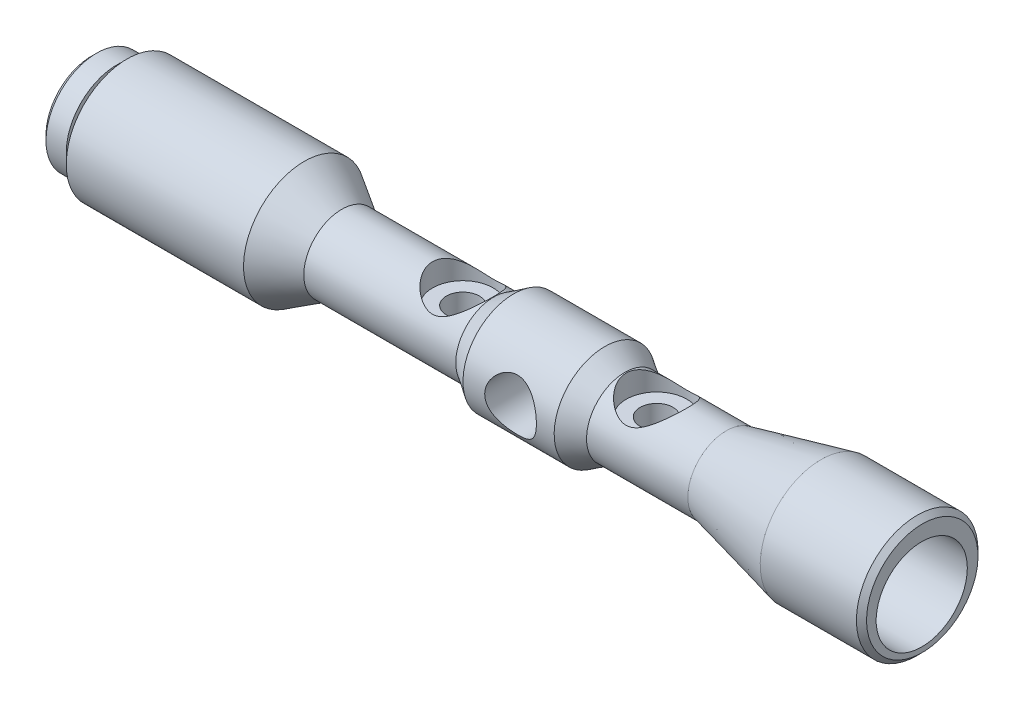
SolidWorks part; units mm, degrees
ref_plane "前视基准面" through (0, 0, 0) normal (0, 0, 1) x (1, 0, 0)
ref_plane "上视基准面" through (0, 0, 0) normal (0, 1, 0) x (1, 0, 0)
ref_plane "右视基准面" through (0, 0, 0) normal (1, 0, 0) x (0, 0, -1)
sketch "草图2" plane through (0, 0, 0) normal (0, 0, 1) x (1, 0, 0)
  line L1 (0, 0) -> (0, 10)
  line L2 (0, 10) -> (5, 10)
  line L3 (5, 10) -> (5, 8.5)
  line L4 (5, 8.5) -> (7, 8.5)
  line L5 (7, 8.5) -> (7, 12)
  line L6 (7, 12) -> (42, 12)
  line L7 (42, 12) -> (49.4, 7.5)
  line L8 (49.4, 7.5) -> (79.4, 7.5)
  line L11 (79.4, 7.5) -> (83.3244, 10)
  line L12 (83.3244, 10) -> (101.3244, 10)
  line L16 (101.3244, 10) -> (105.3, 7.5824)
  line L17 (0, 0) -> (164, 0)
  line L20 (105.3, 7.5824) -> (125.3, 7.5824)
  line L21 (125.3, 7.5824) -> (144, 12)
  line L22 (144, 12) -> (164, 12)
  line L23 (164, 12) -> (164, 0)
  dimension "D1" = 5
  dimension "D10" = 18
  dimension "D2" = 2
  dimension "D3" = 42
  dimension "D4" = 7.4
  dimension "D5" = 10
  dimension "D6" = 30
  dimension "D7" = 12
  dimension "D8" = 7.5
  dimension "D9" = 8.5
  dimension "D11" = 25.9
  dimension "D12" = 10
  dimension "D13" = 12
  dimension "D14" = 20
  dimension "D15" = 18.7
  dimension "D16" = 20
revolve "旋转2" add sketch "草图2" angle 360 about L17
cosmetic thread "装饰螺纹线1" parameters "D2"=17.294
hole_wizard "孔9" positions "草图18" profile "草图19" legacy
sketch "草图18" plane through (0, 0, 0) normal (-1, 0, 0) x (0, 0, 1)
  point P0 (0, 0)
sketch "草图19" plane through (0, 0, 0) normal (0, 1, 0) x (0, 0, 1)
  line L0 (0, 0) -> (0, 52.8868)
  line L1 (0, 52.8868) -> (5, 50)
  line L2 (5, 50) -> (5, 20)
  line L3 (5, 20) -> (7, 20)
  line L4 (7, 0) -> (0, 0)
  line L5 (0, -11.3109) -> (0, 121.1557) construction
  line L6 (0, 52.8868) -> (-5, 50) construction
  line L7 (7, 20) -> (7, 0)
  dimension "直径" = 10
  dimension "深度" = 50
  dimension "柱坑直径" = 14
  dimension "柱坑深度" = 20
  dimension "导头角度" = 120
hole_wizard "M12 螺纹孔1" positions "3D草图7" profile "草图26" tap size "M12" standard "ISO"
sketch3d "3D草图7"
  point P0 (92.712, 0.0036, 10)
sketch "草图26" plane through (92.712, 0.0036, 10) normal (1, 0, 0) x (0, -1, 0.0004)
  line L0 (0, 0) -> (0, 15.0644)
  line L1 (0, 15.0644) -> (5.1, 12)
  line L2 (5.1, 12) -> (5.1, 0)
  line L5 (5.1, 0) -> (0, 0)
  line L10 (0, 15.0644) -> (-5.1, 12) construction
  line L11 (0, -6.35) -> (0, 107.95) construction
  dimension "螺纹孔钻头直径" = 10.2
  dimension "螺纹孔钻头深度" = 12
  dimension "导头角度" = 118
cosmetic thread "孔螺蚊线1" parameters "D1"=12, "D2"=12
chamfer "倒角1" distance 1 angle 45 1 edges at (164, -12, 0)
chamfer "倒角2" distance 1 angle 45 1 edges at (0, -10, 0)
hole_wizard "孔12" positions "草图28" profile "草图27" legacy
sketch "草图28" plane through (164, 0, 0) normal (1, 0, 0) x (0, 0, -1)
  point P0 (-0.1053, -0.9762)
sketch "草图27" plane through (164, -0.9762, 0.1053) normal (0, 1, 0) x (0, 0, -1)
  line L0 (0, 0) -> (0, 42.8868)
  line L1 (0, 42.8868) -> (5, 40)
  line L2 (5, 40) -> (5, 20)
  line L3 (5, 20) -> (9, 20)
  line L4 (9, 0) -> (0, 0)
  line L5 (0, -11.3109) -> (0, 121.1557) construction
  line L6 (0, 42.8868) -> (-5, 40) construction
  line L7 (9, 20) -> (9, 0)
  dimension "直径" = 10
  dimension "深度" = 40
  dimension "柱坑直径" = 18
  dimension "柱坑深度" = 20
  dimension "导头角度" = 120
hole_wizard "孔14" positions "3D草图14" profile "草图38" legacy
sketch3d "3D草图14"
  line L0 (163, 0, 0) -> (39.8271, 0, 0) construction
  circle A0 centre (163, 0, 0) radius 12 construction
  circle A1 centre (164, 0, 0) radius 11 construction
  point P0 (73.3096, 7.5, 0.0003)
  point P8 (151, 0, 0)
  point P14 (175, 0, 0)
  dimension "D1" = 91
sketch "草图38" plane through (73.3096, 7.5, 0.0003) normal (1, 0, 0) x (0, 0, 1)
  line L0 (0, 0) -> (0, 100)
  line L1 (0, 100) -> (3.25, 100)
  line L2 (3.25, 100) -> (3.25, 4.5)
  line L3 (3.25, 4.5) -> (6, 4.5)
  line L4 (6, 4.5) -> (6, 0)
  line L5 (6, 0) -> (0, 0)
  line L6 (0, 110) -> (0, -10) construction
  dimension "直径" = 6.5
  dimension "深度" = 100
  dimension "柱坑直径" = 12
  dimension "柱坑深度" = 4.5
hole_wizard "孔15" positions "3D草图15" profile "草图40" legacy
sketch3d "3D草图15"
  line L0 (163, 0, 0) -> (57.6963, 0, 0)
  circle A3 centre (163, 0, 0) radius 12 construction
  circle A4 centre (164, 0, 0) radius 11 construction
  point P0 (111.5452, 7.5824, 0.0121)
  point P16 (151, 0, 0)
  point P21 (175, 0, 0)
  point P23 (111.5452, 7.5824, 0.0121)
  dimension "D1" = 53
sketch "草图40" plane through (111.5452, 7.5824, 0.0121) normal (1, 0, 0) x (0, -0.0016, 1)
  line L0 (0, 0) -> (0, 100)
  line L1 (0, 100) -> (3.25, 100)
  line L2 (3.25, 100) -> (3.25, 4.5)
  line L3 (3.25, 4.5) -> (6, 4.5)
  line L4 (6, 4.5) -> (6, 0)
  line L5 (6, 0) -> (0, 0)
  line L6 (0, 110) -> (0, -10) construction
  dimension "直径" = 6.5
  dimension "深度" = 100
  dimension "柱坑直径" = 12
  dimension "柱坑深度" = 4.5
